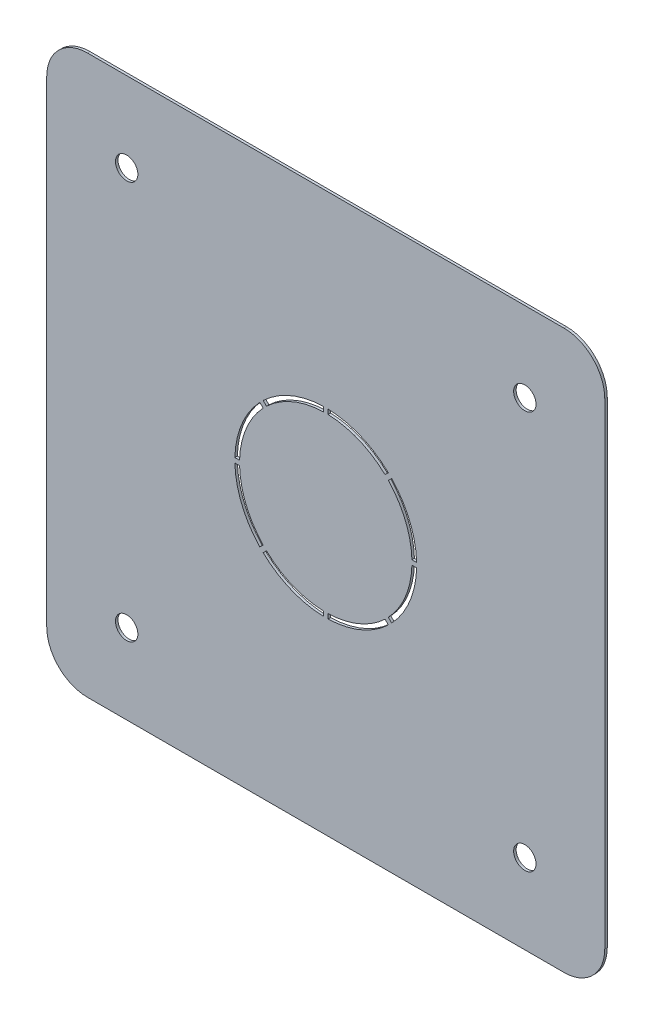
SolidWorks part; units mm, degrees
ref_plane "Front Plane" through (0, 0, 0) normal (0, 0, 1) x (1, 0, 0)
ref_plane "Top Plane" through (0, 0, 0) normal (0, 1, 0) x (1, 0, 0)
ref_plane "Right Plane" through (0, 0, 0) normal (1, 0, 0) x (0, 0, -1)
sketch "Sketch1" plane through (0, 0, 0) normal (0, 0, 1) x (1, 0, 0)
  line L1 (0, 0) -> (178, 0)
  line L2 (0, 0) -> (0, -178)
  line L3 (0, -178) -> (178, -178)
  line L4 (178, 0) -> (178, -178)
  line L5 (25.5, -25.5) -> (152.5, -25.5) construction
  line L6 (25.5, -25.5) -> (25.5, -152.5) construction
  line L7 (25.5, -152.5) -> (152.5, -152.5) construction
  line L8 (152.5, -25.5) -> (152.5, -152.5) construction
  line L9 (25.5, -25.5) -> (152.5, -152.5) construction
  line L10 (25.5, -152.5) -> (152.5, -25.5) construction
  circle A0 centre (25.5, -25.5) radius 3.57
  circle A1 centre (152.5, -25.5) radius 3.57
  circle A2 centre (152.5, -152.5) radius 3.57
  circle A3 centre (25.5, -152.5) radius 3.57
  point P9 (89, -89)
  dimension "D6" = 7.14
  dimension "D1" = 178
  dimension "D2" = 178
  dimension "D3" = 127
  dimension "D4" = 25.5
  dimension "D5" = 25.5
extrude "Boss-Extrude1" add sketch "Sketch1" along normal blind 0.8
fillet "Fillet1" radius 13 4 edges at (0, 0, 0.4) (0, -178, 0.4) (178, -178, 0.4) (178, 0, 0.4)
sketch "Sketch2" plane through (0, 0, 0.8) normal (0, 0, 1) x (1, 0, 0)
  line L0 (165, 0) -> (13, 0) construction
  line L1 (88.25, -60.0097) -> (89.75, -60.0097) construction
  line L3 (88.25, -60.0097) -> (88.25, -61.5102)
  line L5 (89.75, -60.0097) -> (89.75, -61.5102)
  line L6 (110.0296, -69.0311) -> (108.9685, -70.0921)
  line L7 (108.9689, -67.9704) -> (107.9079, -69.0315)
  line L8 (117.9903, -89.75) -> (116.4898, -89.75)
  line L9 (117.9903, -88.25) -> (116.4898, -88.25)
  line L10 (108.9689, -110.0296) -> (107.9079, -108.9685)
  line L11 (110.0296, -108.9689) -> (108.9685, -107.9079)
  line L12 (88.25, -117.9903) -> (88.25, -116.4898)
  line L13 (89.75, -117.9903) -> (89.75, -116.4898)
  line L14 (67.9704, -108.9689) -> (69.0315, -107.9079)
  line L15 (69.0311, -110.0296) -> (70.0921, -108.9685)
  line L16 (60.0097, -88.25) -> (61.5102, -88.25)
  line L17 (60.0097, -89.75) -> (61.5102, -89.75)
  line L18 (69.0311, -67.9704) -> (70.0921, -69.0315)
  line L19 (67.9704, -69.0311) -> (69.0315, -70.0921)
  line L20 (89, -60) -> (89, -89) construction
  circle A0 centre (89, -89) radius 29
  circle A1 centre (89, -89) radius 27.5
  point P4 (89, 0)
  point P10 (89, -60.0097)
  point P11 (89, -89)
  point P42 (89, -89)
  dimension "D2" = 58
  dimension "D4" = 55
  dimension "D1" = 89
  dimension "D3" = 1.5
  dimension "D5" = 8
extrude "Cut-Extrude1" cut sketch "Sketch2" against normal blind 10 contours A1 L3 A0 L18 | A1 L7 A0 L5 | A1 L9 A0 L6 | A1 L13 A0 L10 | A1 L11 A0 L8 | A1 L19 A0 L16 | A1 L17 A0 L14 | A1 L15 A0 L12
equation "\"D4@Sketch1\"=(\"D1@Sketch1\"-\"D3@Sketch1\")/2"
equation "\"D5@Sketch1\"=\"D4@Sketch1\""
